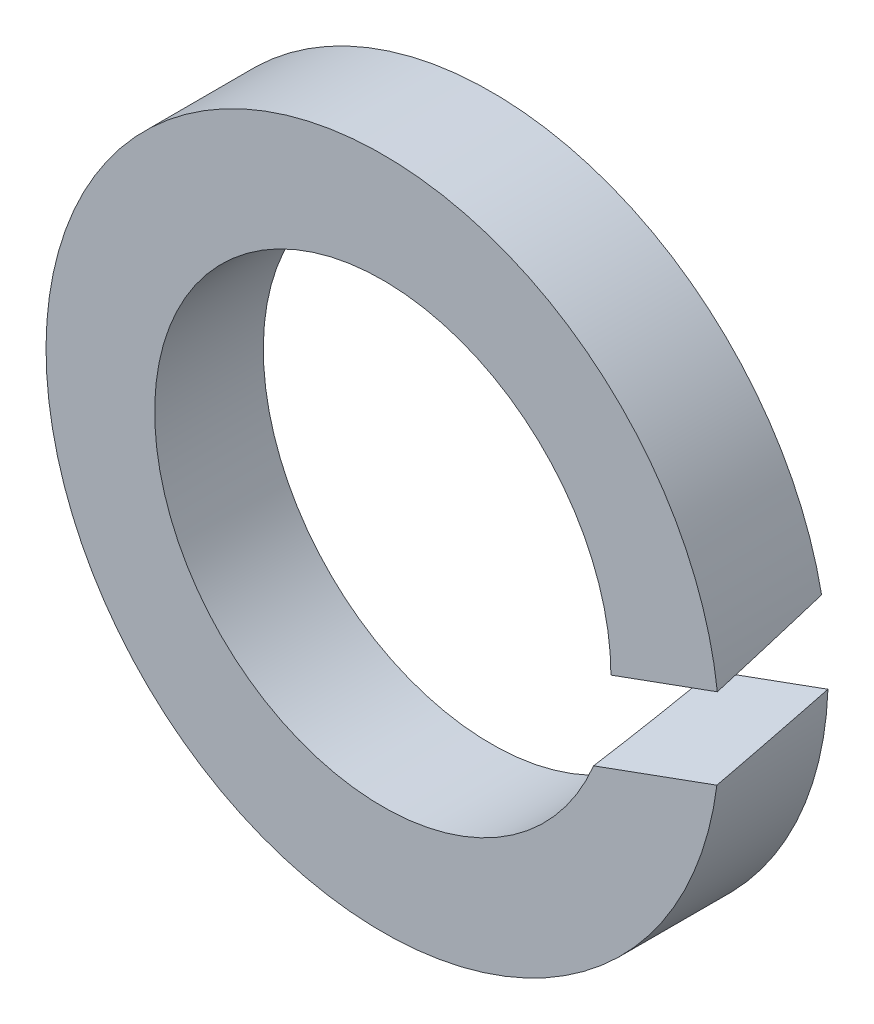
SolidWorks part; units mm, degrees
ref_plane "СПЕРЕДИ" through (0, 0, 0) normal (0, 0, 1) x (1, 0, 0)
ref_plane "СВЕРХУ" through (0, 0, 0) normal (0, 1, 0) x (1, 0, 0)
ref_plane "СПРАВА" through (0, 0, 0) normal (1, 0, 0) x (0, 0, -1)
revolve "Основание-Повернуть" add sketch "Эскиз1" angle 360 about L0
sketch "Эскиз1" plane through (0, 0, 0) normal (1, 0, 0) x (0, 0, -1)
  line L0 (0, 0) -> (40, 0) construction
  line L1 (0, 1.55) -> (0.5, 1.55)
  line L2 (0.5, 1.55) -> (0.5, 1.05)
  line L3 (0.5, 1.05) -> (0, 1.05)
  line L4 (0, 1.55) -> (0, 1.05)
  dimension "d" = 2.1
  dimension "S" = 0.5
  dimension "b" = 0.5
sweep "Вырез-По траектории1" cut profiles "Эскиз2" path "Эскиз3"
sketch "Эскиз2" plane through (0, 0, 0) normal (0, 0, 1) x (1, 0, 0)
  line L0 (0.8505, -0.0726) -> (1.9536, 0.3289)
  line L1 (0.9702, -0.4015) -> (2.0733, 0)
  line L2 (-1.55, 0) -> (2.0733, 0) construction
  line L3 (0.9702, -0.4015) -> (0.8505, -0.0726)
  line L4 (1.9536, 0.3289) -> (2.0733, 0)
  line L5 (0, 1.55) -> (0, -1.55) construction
  circle A1 centre (0, 0) radius 1.05 construction
  circle A2 centre (0, 0) radius 1.55 construction
  point P1 (1.05, 0)
  dimension "D1" = 70
  dimension "m" = 0.35
sketch "Эскиз3" plane through (0, 0, 0) normal (1, 0, 0) x (0, 0, -1)
  line L0 (0, 0) -> (20, 5.359)
  line L1 (0, 1.55) -> (0, -1.55) construction
  dimension "D1" = 75
  dimension "D2" = 20
